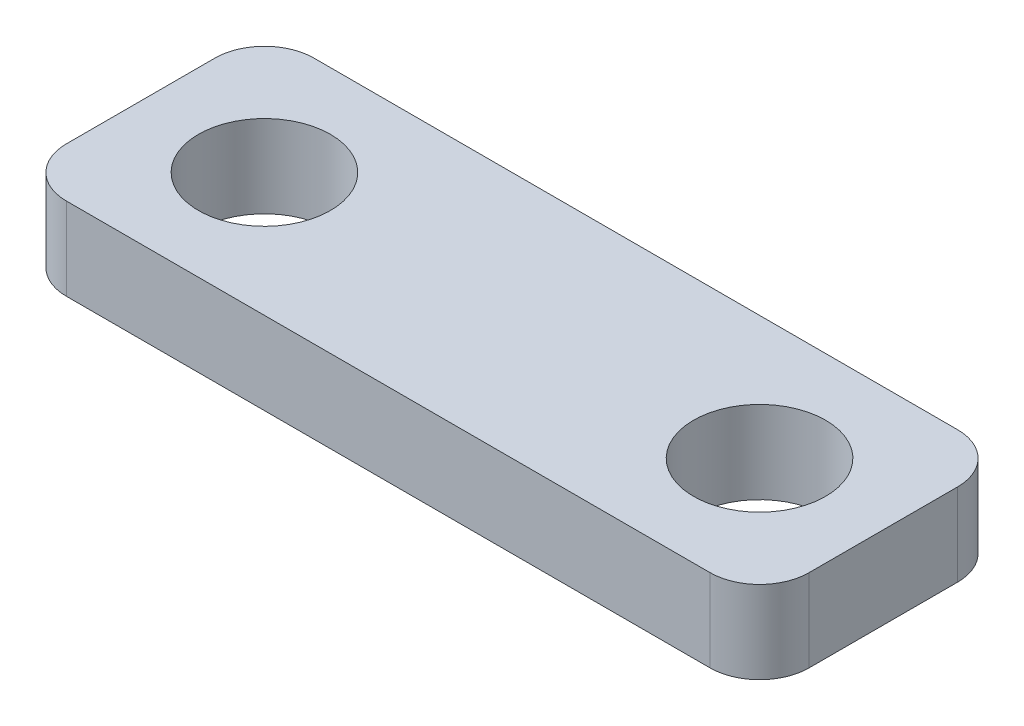
SolidWorks part; units mm, degrees
material "Aleación 1060"
ref_plane "Alzado" through (0, 0, 0) normal (0, 0, 1) x (1, 0, 0)
ref_plane "Planta" through (0, 0, 0) normal (0, 1, 0) x (1, 0, 0)
ref_plane "Vista lateral" through (0, 0, 0) normal (1, 0, 0) x (0, 0, -1)
sketch "Croquis2" plane through (0, 0, 0) normal (0, 1, 0) x (1, 0, 0)
  line L1 (-22.5, -7.5) -> (22.5, -7.5)
  line L2 (-22.5, -7.5) -> (-22.5, 7.5)
  line L3 (-22.5, 7.5) -> (22.5, 7.5)
  line L4 (22.5, -7.5) -> (22.5, 7.5)
  line L5 (-22.5, -7.5) -> (22.5, 7.5) construction
  line L6 (-22.5, 7.5) -> (22.5, -7.5) construction
  point P0 (0, 0)
  dimension "D1" = 15
  dimension "D2" = 45
extrude "Saliente-Extruir1" add sketch "Croquis2" along normal blind 5
fillet "Redondeo1" radius 3 4 edges at (-22.5, 2.5, 7.5) (22.5, 2.5, 7.5) (22.5, 2.5, -7.5) (-22.5, 2.5, -7.5)
sketch "Croquis3" plane through (0, 5, 0) normal (0, 1, 0) x (1, 0, 0)
  line L1 (22.5, -4.5) -> (22.5, 4.5) construction
  line L2 (-22.5, 4.5) -> (-22.5, -4.5) construction
  circle A0 centre (-15, 0) radius 4
  circle A1 centre (15, 0) radius 4
  dimension "D1" = 8
  dimension "D2" = 8
  dimension "D3" = 7.5
  dimension "D4" = 7.5
extrude "Cortar-Extruir1" cut sketch "Croquis3" against normal mid plane 20
